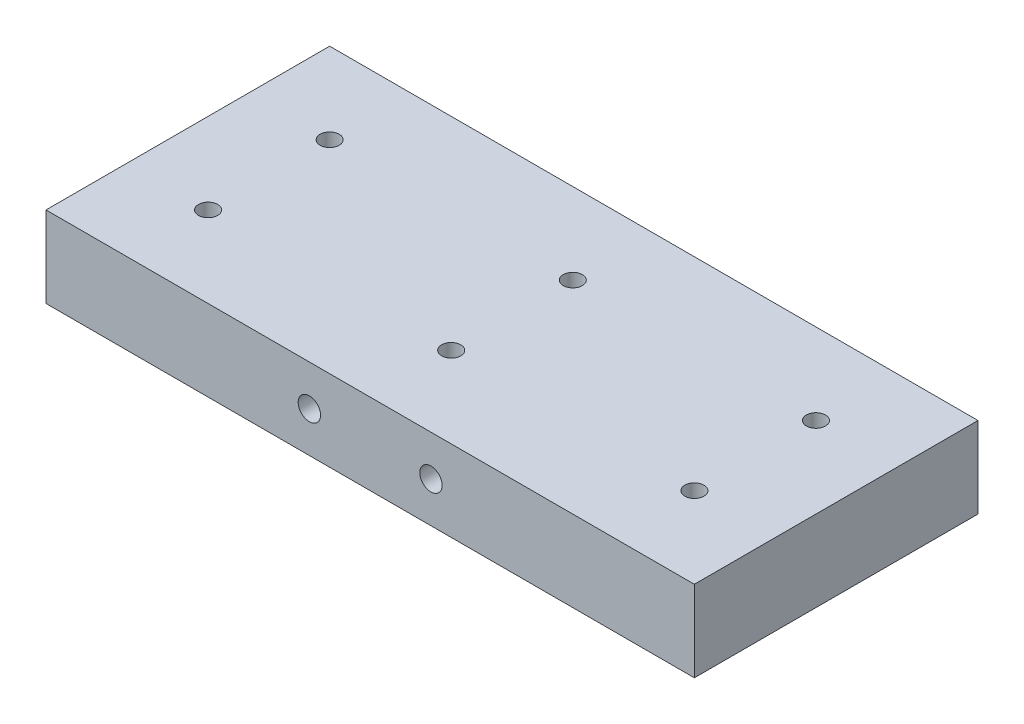
SolidWorks part; units mm, degrees
material "6061 Alloy"
ref_plane "Front" through (0, 0, 0) normal (0, 0, 1) x (1, 0, 0)
ref_plane "Top" through (0, 0, 0) normal (0, 1, 0) x (1, 0, 0)
ref_plane "Right" through (0, 0, 0) normal (1, 0, 0) x (0, 0, -1)
sketch "Sketch1" plane through (0, 0, 0) normal (1, 0, 0) x (0, 0, -1)
  line L1 (-22.225, -6.35) -> (22.225, -6.35)
  line L2 (-22.225, -6.35) -> (-22.225, 6.35)
  line L3 (-22.225, 6.35) -> (22.225, 6.35)
  line L4 (22.225, -6.35) -> (22.225, 6.35)
  line L5 (-22.225, -6.35) -> (22.225, 6.35) construction
  line L6 (-22.225, 6.35) -> (22.225, -6.35) construction
  point P0 (0, 0)
  dimension "D1" = 44.45
  dimension "D2" = 12.7
extrude "Boss-Extrude1" add sketch "Sketch1" along normal mid plane 101.6
hole_wizard "M3-10 Threaded Hole" positions "Sketch3" profile "Sketch2" hole size "Ø3.0" standard "ANSI Metric"
sketch "Sketch3" plane through (0, 6.35, 0) normal (0, 1, 0) x (1, 0, 0)
  line L0 (-50.8, -9.525) -> (50.8, -9.525) construction
  line L4 (0, -22.225) -> (0, 22.225) construction
  line L5 (50.8, -22.225) -> (-50.8, -22.225) construction
  line L6 (50.8, 22.225) -> (-50.8, 22.225) construction
  line L8 (-50.8, 9.525) -> (50.8, 9.525) construction
  line L9 (-50.8, 22.225) -> (-50.8, -22.225) construction
  line L10 (50.8, 22.225) -> (50.8, -22.225) construction
  point P12 (-38.1, -9.525)
  point P22 (0, -9.525)
  point P23 (38.1, -9.525)
  point P33 (-38.1, 9.525)
  point P35 (0, 9.525)
  point P37 (38.1, 9.525)
  dimension "D1" = 38.1
  dimension "D3" = 12.7
  dimension "D4" = 19.05
sketch "Sketch2" plane through (-38.1, 6.35, 9.525) normal (1, 0, 0) x (0, 0, 1)
  line L0 (0, 0) -> (0, 7.2513)
  line L1 (0, 7.2513) -> (1.5, 6.35)
  line L2 (1.5, 6.35) -> (1.5, 0)
  line L5 (1.5, 0) -> (0, 0)
  line L10 (0, 7.2513) -> (-1.5, 6.35) construction
  line L11 (0, -6.35) -> (0, 107.95) construction
  dimension "Hole Dia." = 3
  dimension "Hole Depth" = 6.35
  dimension "Drill Angle" = 118
hole_wizard "#6-32 Threaded Hole" positions "Sketch5" profile "Sketch4" hole size "#97" standard "ANSI Inch" end condition through all
sketch "Sketch5" plane through (0, 0, 22.225) normal (0, 0, 1) x (1, 0, 0)
  line L0 (-50.8, 0) -> (50.8, 0) construction
  line L1 (-50.8, 6.35) -> (-50.8, -6.35) construction
  line L2 (50.8, 6.35) -> (50.8, -6.35) construction
  line L3 (0, -6.35) -> (0, 6.35) construction
  line L4 (50.8, -6.35) -> (-50.8, -6.35) construction
  line L5 (50.8, 6.35) -> (-50.8, 6.35) construction
  point P0 (-9.525, 0)
  point P2 (9.525, 0)
  dimension "D1" = 19.05
sketch "Sketch4" plane through (-9.525, 0, 22.225) normal (1, 0, 0) x (0, -1, 0)
  line L0 (0, 0) -> (0, 44.45)
  line L1 (0, 44.45) -> (1.7551, 44.45)
  line L2 (1.7551, 44.45) -> (1.7551, 0)
  line L5 (1.7551, 0) -> (0, 0)
  line L11 (0, -6.35) -> (0, 107.95) construction
  dimension "Thru Hole Dia." = 3.5103
  dimension "Thru Hole Depth" = 44.45
